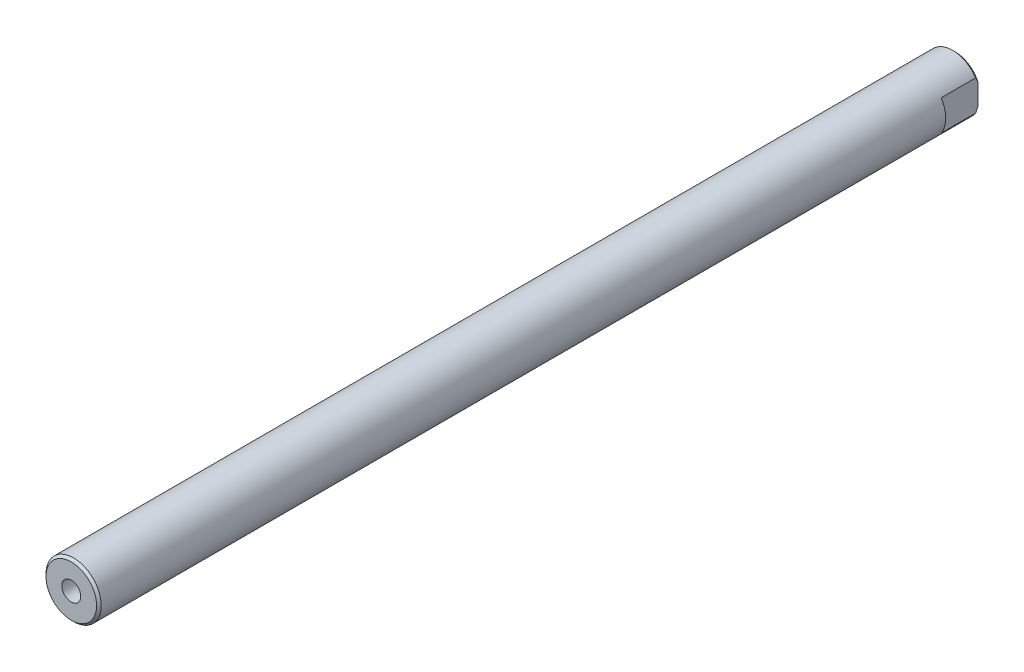
SolidWorks part; units mm, degrees
ref_plane "Front" through (0, 0, 0) normal (0, 0, 1) x (1, 0, 0)
ref_plane "Top" through (0, 0, 0) normal (0, 1, 0) x (1, 0, 0)
ref_plane "Right" through (0, 0, 0) normal (1, 0, 0) x (0, 0, -1)
sketch "Sketch1" plane through (0, 0, 0) normal (0, 0, 1) x (1, 0, 0)
  circle A0 centre (0, 0) radius 9.525
  dimension "D1" = 19.05
extrude "Extrude1" add sketch "Sketch1" along normal blind 304.8
chamfer "Chamfer1" distance 0.7937 angle 45 2 edges at (9.525, 0, 304.8) (9.525, 0, 0)
hole_wizard "5/16-18 Tapped Hole1" positions "Sketch3" profile "Sketch2" tap size "5/16-18" standard "Ansi Inch"
sketch "Sketch3" plane through (0, 0, 304.8) normal (0, 0, 1) x (1, 0, 0)
  point P0 (0, 0)
sketch "Sketch2" plane through (0, 0, 304.8) normal (1, 0, 0) x (0, -1, 0)
  line L0 (0, 0) -> (0, 26.5674)
  line L1 (0, 26.5674) -> (3.2639, 24.6063)
  line L2 (3.2639, 24.6063) -> (3.2639, 0)
  line L5 (3.2639, 0) -> (0, 0)
  line L10 (0, 26.5674) -> (-3.2639, 24.6063) construction
  line L11 (0, -6.35) -> (0, 107.95) construction
  dimension "Tap Drill Dia." = 6.5278
  dimension "Tap Drill Depth" = 24.6063
  dimension "Drill Angle" = 118
cosmetic thread "Hole Thread1" parameters "D1"=15.875, "D2"=7.9375
sketch "Sketch4" plane through (0, 0, 0) normal (0, 0, -1) x (-1, 0, 0)
  line L2 (-7.9375, 5.2651) -> (-7.9375, -5.2651)
  line L4 (7.9375, 5.2651) -> (7.9375, -5.2651)
  circle A0 centre (0, 0) radius 9.525 construction
  arc A1 (7.9375, -5.2651) -> (7.9375, 5.2651) centre (0, 0) ccw
  arc A2 (-7.9375, 5.2651) -> (-7.9375, -5.2651) centre (0, 0) ccw
  dimension "D1" = 15.875
extrude "Cut-Extrude1" cut sketch "Sketch4" against normal blind 12.7
